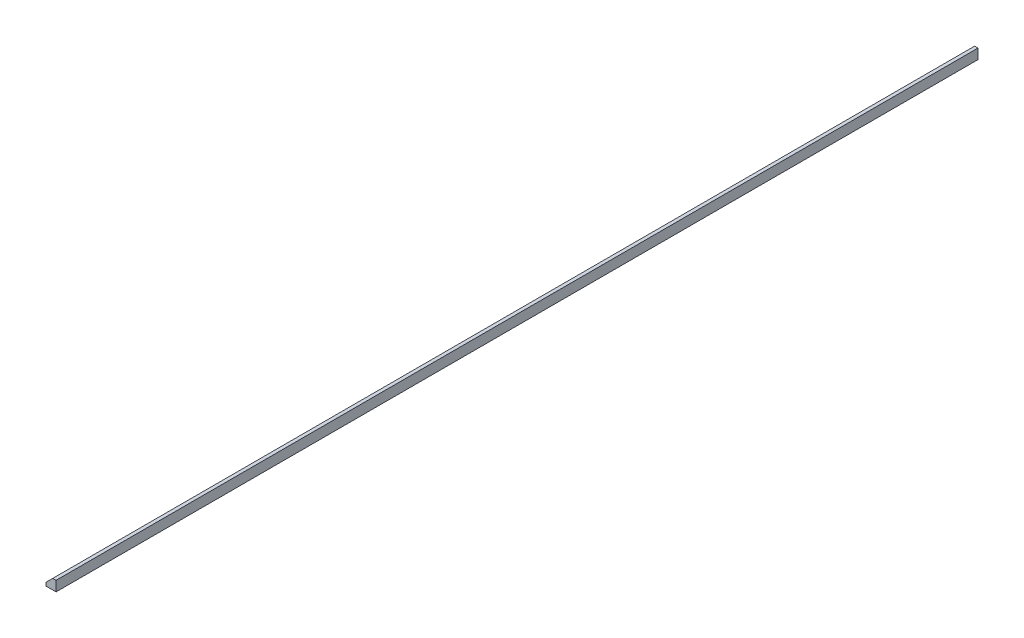
SolidWorks part; units mm, degrees
ref_plane "Plan de face" through (0, 0, 0) normal (0, 0, 1) x (1, 0, 0)
ref_plane "Plan de dessus" through (0, 0, 0) normal (0, 1, 0) x (1, 0, 0)
ref_plane "Plan de droite" through (0, 0, 0) normal (1, 0, 0) x (0, 0, -1)
sketch "Esquisse1" plane through (0, 0, 0) normal (0, 0, 1) x (1, 0, 0)
  line L1 (0, 0) -> (12, 0)
  line L2 (0, 0) -> (0, 12)
  line L3 (0, 12) -> (12, 12)
  line L4 (12, 0) -> (12, 12)
  dimension "D1" = 12
  dimension "D2" = 12
extrude "Boss.-Extru.1" add sketch "Esquisse1" along normal blind 1100
chamfer "Chanfrein1" distance 8 angle 45 1 edges at (0, 12, 550)
